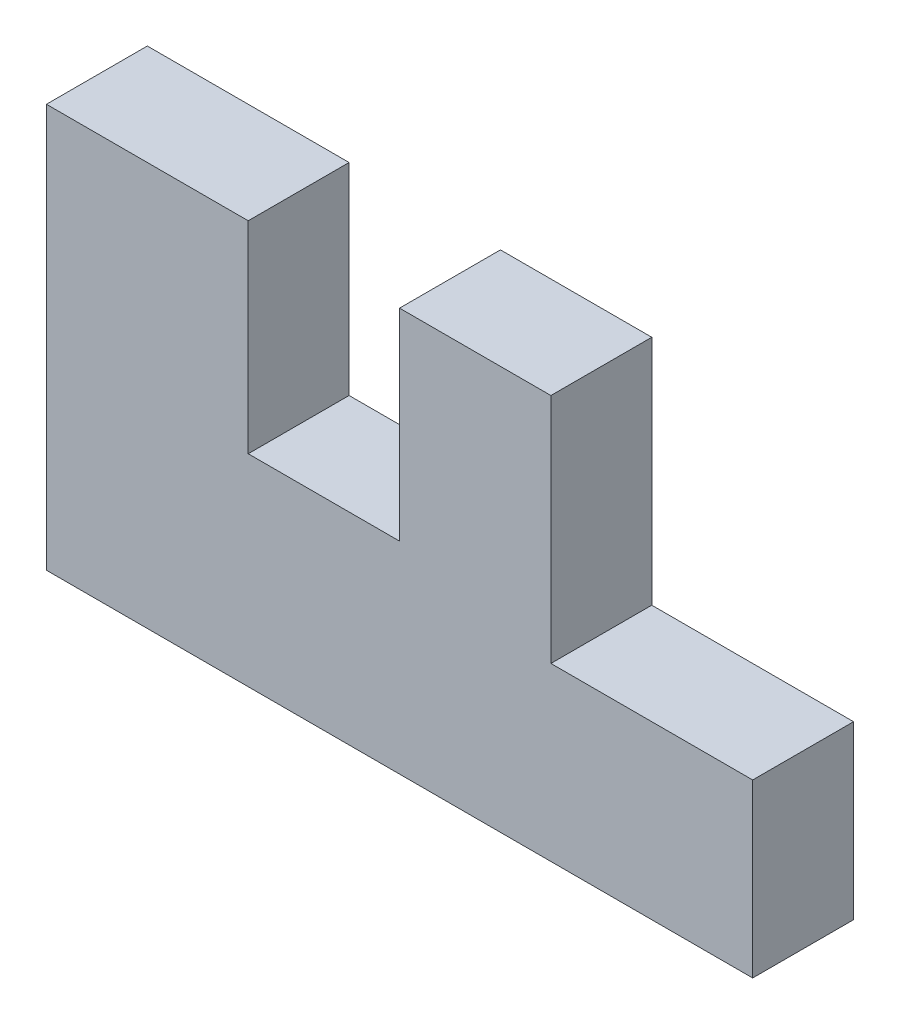
SolidWorks part; units mm, degrees
ref_plane "Front Plane" through (0, 0, 0) normal (0, 0, 1) x (1, 0, 0)
ref_plane "Top Plane" through (0, 0, 0) normal (0, 1, 0) x (1, 0, 0)
ref_plane "Right Plane" through (0, 0, 0) normal (1, 0, 0) x (0, 0, -1)
sketch "Sketch1" plane through (0, 0, 0) normal (0, 0, 1) x (1, 0, 0)
  line L0 (0, 0) -> (0, 50.8)
  line L1 (0, 0) -> (88.9, 0)
  line L2 (0, 50.8) -> (25.4, 50.8)
  line L3 (25.4, 50.8) -> (25.4, 25.4)
  line L4 (25.4, 25.4) -> (44.45, 25.4)
  line L5 (44.45, 25.4) -> (44.45, 50.8)
  line L6 (44.45, 50.8) -> (63.5, 50.8)
  line L7 (63.5, 50.8) -> (63.5, 21.59)
  line L8 (63.5, 21.59) -> (88.9, 21.59)
  line L9 (88.9, 21.59) -> (88.9, 0)
  dimension "D1" = 50.8
  dimension "D2" = 88.9
  dimension "D3" = 63.5
  dimension "D4" = 44.45
  dimension "D5" = 25.4
  dimension "D6" = 25.4
  dimension "D7" = 21.59
extrude "Boss-Extrude1" add sketch "Sketch1" along normal blind 12.7
